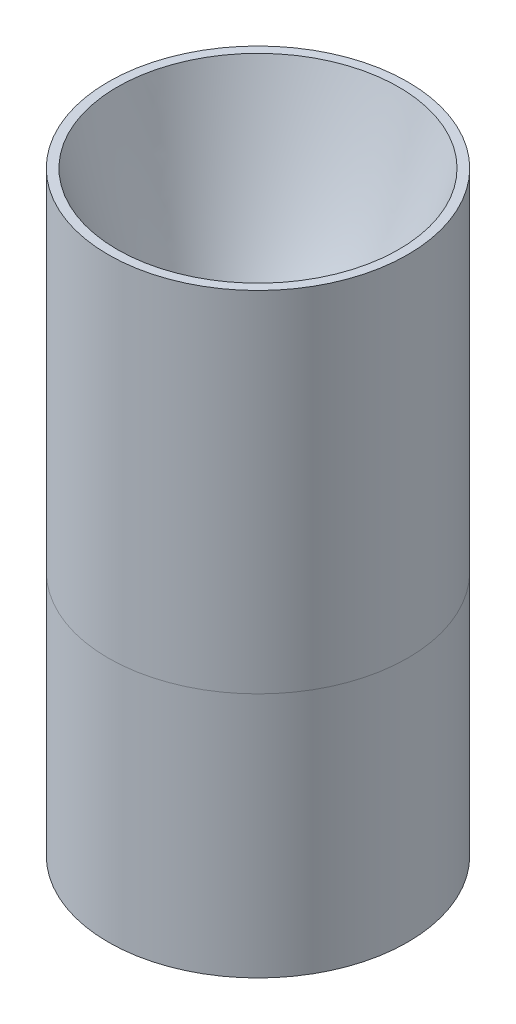
SolidWorks part; units mm, degrees
ref_plane "Front Plane" through (0, 0, 0) normal (0, 0, 1) x (1, 0, 0)
ref_plane "Top Plane" through (0, 0, 0) normal (0, 1, 0) x (1, 0, 0)
ref_plane "Right Plane" through (0, 0, 0) normal (1, 0, 0) x (0, 0, -1)
sketch "Sketch1" plane through (0, 0, 0) normal (0, 0, 1) x (1, 0, 0)
  line L0 (24.01, 0) -> (0, 0) construction
  line L1 (71.6385, 109.9273) -> (76.2, 109.9273)
  line L4 (53.7925, -59.7277) -> (53.7925, -212.1277)
  line L9 (76.2, 109.9273) -> (76.2, -212.1277)
  line L10 (76.2, -212.1277) -> (53.7925, -212.1277)
  line L11 (0, 0) -> (0, -107.6606) construction
  spline S0 degree 2 poles (26.7062, 6.5092) (49.1723, 34.636) (71.6385, 109.9273) knots 0 0 0 1 1 1 construction
  spline S1 degree 2 poles (26.7062, 6.5092) (49.1723, 34.636) (71.6385, 109.9273) knots 0 0 0 1 1 1
  spline S2 degree 4 poles (24.0378, -0.7181) (24.0369, -0.702) (24.0352, -0.674) (24.0319, -0.6548) (24.026, -0.5168) (24.0168, -0.4371) (24.0103, -0.1068) (24.0089, 0.0016) (24.013, 0.2676) (24.0194, 0.4271) (24.0315, 0.6468) (24.0524, 0.9014) (24.0861, 1.2025) (24.1374, 1.5421) (24.2015, 1.881) (24.2781, 2.2164) (24.3673, 2.5492) (24.4687, 2.8781) (24.5826, 3.2033) (24.7081, 3.5236) (24.8462, 3.8397) (24.995, 4.1493) (25.1569, 4.4548) (25.3274, 4.7513) (25.5134, 5.0457) (25.7027, 5.3255) (25.9153, 5.6107) (26.0898, 5.8329) (26.2773, 6.05) (26.4155, 6.2086) (26.6679, 6.4727) (26.7479, 6.5524) (27.0125, 6.8058) (27.099, 6.8781) (27.1963, 6.9666) (27.2147, 6.9802) (27.2373, 7.0002) knots 0 0 0 0 0 0.005192 0.010384 0.020768 0.041536 0.082569 0.102427 0.122284 0.142142 0.162 0.201716 0.241431 0.281147 0.320863 0.360578 0.400294 0.44001 0.479725 0.519441 0.559156 0.598872 0.638588 0.678303 0.718019 0.757735 0.79745 0.837166 0.857024 0.876882 0.916597 0.958047 0.979024 0.989512 1 1 1 1 1 construction
  spline S3 degree 4 poles (24.01, 0) (24.01, 0.0359) (24.0105, 0.1101) (24.013, 0.2676) (24.0194, 0.4271) (24.0315, 0.6468) (24.0524, 0.9014) (24.0861, 1.2025) (24.1374, 1.5421) (24.2015, 1.881) (24.2781, 2.2164) (24.3673, 2.5492) (24.4687, 2.8781) (24.5826, 3.2033) (24.7081, 3.5236) (24.8462, 3.8397) (24.995, 4.1493) (25.1569, 4.4548) (25.3274, 4.7513) (25.5134, 5.0457) (25.7027, 5.3255) (25.9153, 5.6107) (26.0898, 5.8329) (26.2773, 6.05) (26.4155, 6.2086) (26.5814, 6.3821) (26.6555, 6.4585) (26.7062, 6.5092) knots 0.082569 0.082569 0.082569 0.082569 0.082569 0.102427 0.122284 0.142142 0.162 0.201716 0.241431 0.281147 0.320863 0.360578 0.400294 0.44001 0.479725 0.519441 0.559156 0.598872 0.638588 0.678303 0.718019 0.757735 0.79745 0.837166 0.857024 0.876882 0.916597 0.916597 0.916597 0.916597 0.916597
  spline S4 degree 4 poles (24.1192, 2.8078) (24.1123, 2.7164) (24.0991, 2.5516) (24.0751, 2.1752) (24.0462, 1.6879) (24.0258, 1.1016) (24.0139, 0.6554) (24.0097, 0.1102) (24.0097, -0.1001) (24.0129, -0.5432) (24.0192, -0.8242) (24.0287, -1.1948) (24.0414, -1.5134) (24.0572, -1.8619) (24.0761, -2.1937) (24.1038, -2.6181) (24.1432, -3.122) (24.2142, -3.88) (24.3341, -4.8865) (24.5104, -6.0567) (24.7618, -7.3852) (25.0627, -8.7036) (25.4127, -10.0096) (25.8113, -11.3018) (26.2579, -12.5781) (26.7519, -13.8369) (27.2926, -15.0762) (27.8794, -16.2946) (28.5111, -17.4899) (29.1875, -18.6613) (29.9064, -19.8057) (30.669, -20.9239) (31.3701, -21.8744) (31.9997, -22.6734) (32.5351, -23.3204) (32.9832, -23.84) (33.4194, -24.3298) (33.8468, -24.7885) (34.1565, -25.1139) (34.523, -25.486) (34.677, -25.64) (35.0618, -26.0189) (35.3885, -26.3288) (35.8159, -26.7274) (36.1505, -27.0244) (36.4301, -27.2709) (36.5574, -27.38) (36.6257, -27.4388) (36.6605, -27.4687) knots 0 0 0 0 0 0.010393 0.020785 0.041571 0.062104 0.072371 0.082638 0.092575 0.102512 0.112449 0.122387 0.132324 0.142261 0.152198 0.162135 0.18201 0.201884 0.241633 0.281382 0.32113 0.360879 0.400628 0.440377 0.480126 0.519874 0.559623 0.599372 0.639121 0.67887 0.718618 0.758367 0.798116 0.81799 0.837865 0.857739 0.877613 0.897488 0.907425 0.917362 0.927629 0.937896 0.958429 0.979215 0.989607 0.994804 1 1 1 1 1 construction
  spline S5 degree 4 poles (24.01, 0) (24.01, -0.0705) (24.0105, -0.2136) (24.0129, -0.5432) (24.0192, -0.8242) (24.0287, -1.1948) (24.0414, -1.5134) (24.0572, -1.8619) (24.0761, -2.1937) (24.1038, -2.6181) (24.1432, -3.122) (24.2142, -3.88) (24.3341, -4.8865) (24.5104, -6.0567) (24.7618, -7.3852) (25.0627, -8.7036) (25.4127, -10.0096) (25.8113, -11.3018) (26.2579, -12.5781) (26.7519, -13.8369) (27.2926, -15.0762) (27.8794, -16.2946) (28.5111, -17.4899) (29.1875, -18.6613) (29.9064, -19.8057) (30.669, -20.9239) (31.3701, -21.8744) (31.9997, -22.6734) (32.5351, -23.3204) (32.9832, -23.84) (33.4194, -24.3298) (33.8468, -24.7885) (34.1565, -25.1139) (34.4478, -25.4096) (34.5473, -25.5099) (34.5972, -25.5598) knots 0.082638 0.082638 0.082638 0.082638 0.082638 0.092575 0.102512 0.112449 0.122387 0.132324 0.142261 0.152198 0.162135 0.18201 0.201884 0.241633 0.281382 0.32113 0.360879 0.400628 0.440377 0.480126 0.519874 0.559623 0.599372 0.639121 0.67887 0.718618 0.758367 0.798116 0.81799 0.837865 0.857739 0.877613 0.897488 0.907425 0.917362 0.917362 0.917362 0.917362 0.917362
  spline S6 degree 1 poles (34.5972, -25.5598) (43.2048, -34.1675) knots 0 0 1 1 construction
  spline S7 degree 1 poles (34.5972, -25.5598) (43.2048, -34.1675) knots 0 0 1 1
  spline S8 degree 4 poles (53.6833, -62.5354) (53.6902, -62.4466) (53.7033, -62.2738) (53.7213, -62.0018) (53.7419, -61.6601) (53.7589, -61.2922) (53.7725, -60.9659) (53.7826, -60.5754) (53.7894, -60.2941) (53.7927, -59.8333) (53.7927, -59.6305) (53.7896, -59.1817) (53.7832, -58.905) (53.7737, -58.5327) (53.7611, -58.213) (53.7414, -57.7818) (53.7113, -57.2811) (53.6671, -56.6882) (53.5882, -55.8486) (53.4884, -55.0083) (53.3676, -54.1726) (53.1977, -53.1726) (53.003, -52.1776) (52.7773, -51.1887) (52.5209, -50.2076) (52.2402, -49.2332) (51.9353, -48.2661) (51.5445, -47.1493) (51.0505, -45.8906) (50.5097, -44.6511) (49.923, -43.4329) (49.2911, -42.2373) (48.6151, -41.0663) (47.8954, -39.9211) (47.134, -38.8042) (46.4308, -37.8516) (45.8045, -37.0558) (45.2637, -36.4035) (44.8261, -35.8944) (44.4257, -35.4472) (44.0924, -35.0848) (43.7849, -34.7605) (43.585, -34.5517) (43.2762, -34.2384) (43.1268, -34.0891) (42.7386, -33.7068) (42.415, -33.3999) (41.985, -32.9988) (41.6521, -32.7035) (41.3716, -32.4561) (41.2447, -32.3474) (41.1763, -32.2885) (41.1415, -32.2585) knots 0 0 0 0 0 0.010393 0.020785 0.031178 0.041571 0.051838 0.062104 0.072371 0.082638 0.092575 0.102512 0.112449 0.122387 0.132324 0.142261 0.162135 0.18201 0.201884 0.241633 0.261507 0.281382 0.32113 0.360879 0.380754 0.400628 0.440377 0.480126 0.519874 0.559623 0.599372 0.639121 0.67887 0.718618 0.758367 0.798116 0.81799 0.837865 0.857739 0.877613 0.887551 0.897488 0.907425 0.917362 0.927629 0.937896 0.958429 0.979215 0.989607 0.994804 1 1 1 1 1 construction
  spline S9 degree 4 poles (53.7925, -59.7277) (53.7925, -59.6571) (53.7919, -59.5156) (53.7896, -59.1817) (53.7832, -58.905) (53.7737, -58.5327) (53.7611, -58.213) (53.7414, -57.7818) (53.7113, -57.2811) (53.6671, -56.6882) (53.5882, -55.8486) (53.4884, -55.0083) (53.3676, -54.1726) (53.1977, -53.1726) (53.003, -52.1776) (52.7773, -51.1887) (52.5209, -50.2076) (52.2402, -49.2332) (51.9353, -48.2661) (51.5445, -47.1493) (51.0505, -45.8906) (50.5097, -44.6511) (49.923, -43.4329) (49.2911, -42.2373) (48.6151, -41.0663) (47.8954, -39.9211) (47.134, -38.8042) (46.4308, -37.8516) (45.8045, -37.0558) (45.2637, -36.4035) (44.8261, -35.8944) (44.4257, -35.4472) (44.0924, -35.0848) (43.7849, -34.7605) (43.585, -34.5517) (43.3553, -34.3187) (43.2547, -34.2173) (43.2048, -34.1675) knots 0.082638 0.082638 0.082638 0.082638 0.082638 0.092575 0.102512 0.112449 0.122387 0.132324 0.142261 0.162135 0.18201 0.201884 0.241633 0.261507 0.281382 0.32113 0.360879 0.380754 0.400628 0.440377 0.480126 0.519874 0.559623 0.599372 0.639121 0.67887 0.718618 0.758367 0.798116 0.81799 0.837865 0.857739 0.877613 0.887551 0.897488 0.907425 0.917362 0.917362 0.917362 0.917362 0.917362
  spline S10 degree 2 poles (36.8348, 6.4922) (58.5923, 47.8769) (81.7275, 109.9275) knots 0.477621 0.477621 0.477621 0.998065 0.998065 0.998065 construction
  dimension "D1" = 152.4
  dimension "D2" = 24.01
  dimension "D3" = 152.4
revolve "Revolve2" add sketch "Sketch1" angle 360 about L11
other "shorten_chamber_.75in" face at (0, -212.1277, 76.2) parameters "D1"=19.05
hole_wizard "3/8-24 Tapped Hole1" [suppressed] positions "Sketch3" profile "Sketch4" tap size "3/8-24" standard "ANSI Inch"
sketch "Sketch3" plane through (0, -193.0777, 0) normal (0, -1, 0) x (-1, 0, 0)
  circle A1 centre (0, 0) radius 66.675 construction
  point P10 (-66.675, 0)
  dimension "D1" = 133.35
sketch "Sketch4" plane through (66.675, -193.0777, 0) normal (1, 0, 0) x (0, 0, -1)
  line L0 (0, 0) -> (0, 27.5347)
  line L1 (0, 27.5347) -> (4.2164, 25.0012)
  line L2 (4.2164, 25.0012) -> (4.2164, 0)
  line L5 (4.2164, 0) -> (0, 0)
  line L10 (0, 27.5347) -> (-4.2164, 25.0012) construction
  line L11 (0, -6.35) -> (0, 107.95) construction
  dimension "Tap Drill Dia." = 8.4328
  dimension "Tap Drill Depth" = 25.0012
  dimension "Drill Angle" = 118
cosmetic thread "Hole Thread1" [suppressed] parameters "D1"=20, "D2"=9.525
pattern_circular "CirPattern1" [suppressed] count 8 over 360
cosmetic thread "Hole Thread2" [suppressed] parameters "D1"=20, "D2"=9.525
cosmetic thread "Hole Thread3" [suppressed] parameters "D1"=20, "D2"=9.525
cosmetic thread "Hole Thread4" [suppressed] parameters "D1"=20, "D2"=9.525
cosmetic thread "Hole Thread5" [suppressed] parameters "D1"=20, "D2"=9.525
cosmetic thread "Hole Thread6" [suppressed] parameters "D1"=20, "D2"=9.525
cosmetic thread "Hole Thread7" [suppressed] parameters "D1"=20, "D2"=9.525
cosmetic thread "Hole Thread8" [suppressed] parameters "D1"=20, "D2"=9.525
sketch "Sketch8" [suppressed] plane through (0, -212.1275, 0) normal (0, -1, 0) x (1, 0, 0)
  circle A0 centre (0, 0) radius 53.8815 construction
  circle A1 centre (0, 0) radius 76.49 construction
  circle A2 centre (0, 0) radius 65.2002 construction
  dimension "D1" = 107.7631
  dimension "D2" = 130.4004
  dimension "D3" = 152.98
sketch "Sketch9" [suppressed] plane through (0, -212.1277, 0) normal (0, -1, 0) x (1, 0, 0)
  circle A0 centre (0, 0) radius 53.8815
  circle A1 centre (0, 0) radius 56.8815
  dimension "D1" = 3
extrude "Cut-Extrude1" [suppressed] cut sketch "Sketch9" against normal blind 6
hole_wizard "1/4 (0.2500) Dowel Hole1" [suppressed] positions "Sketch11" profile "Sketch12" hole size "1/4" standard "ANSI Inch"
sketch "Sketch11" [suppressed] plane through (0, -212.1277, 0) normal (0, -1, 0) x (-1, 0, 0)
  line L6 (0, 0) -> (61.5997, -25.5154) construction
  line L8 (0, 0) -> (-61.5997, 25.5154) construction
  line L9 (0, 0) -> (-66.675, 0) construction
  circle A0 centre (0, 0) radius 66.675 construction
  point P22 (61.5997, -25.5154)
  point P28 (-61.5997, 25.5154)
  dimension "D1" = 22.5
sketch "Sketch12" plane through (61.5997, -212.1277, -25.5154) normal (1, 0, 0) x (0, 0, -1)
  line L0 (0, 0) -> (0, 11.829)
  line L1 (0, 11.829) -> (3.2004, 9.906)
  line L2 (3.2004, 9.906) -> (3.2004, 0)
  line L5 (3.2004, 0) -> (0, 0)
  line L10 (0, 11.829) -> (-3.2004, 9.906) construction
  line L11 (0, -6.35) -> (0, 107.95) construction
  dimension "Hole Dia." = 6.4008
  dimension "Hole Depth" = 9.906
  dimension "Drill Angle" = 118
sketch "Sketch14" plane through (0, -193.0777, 0) normal (0, -1, 0) x (1, 0, 0)
  circle A0 centre (0, 0) radius 53.7925 construction
  circle A1 centre (0, 0) radius 53.7925 construction
  circle A2 centre (0, 0) radius 55.38
  circle A3 centre (0, 0) radius 57.412
  dimension "D1" = 1.5875
  dimension "D2" = 2.032
extrude "gasket_groove" [suppressed] cut sketch "Sketch14" against normal blind 1.27
sketch "Sketch15" plane through (0, 0, 0) normal (0, 0, 1) x (1, 0, 0)
  line L0 (-76.2, -67.8727) -> (76.2, -67.8727)
  line L1 (-76.2, 109.9273) -> (-76.2, -193.0777) construction
  line L2 (76.2, -193.0777) -> (76.2, 109.9273) construction
  line L3 (71.6385, 109.9273) -> (-71.6385, 109.9273) construction
  dimension "D1" = 177.8
split "Split1" trim tools "Sketch15" bodies to split 107 resulting bodies 108 109
